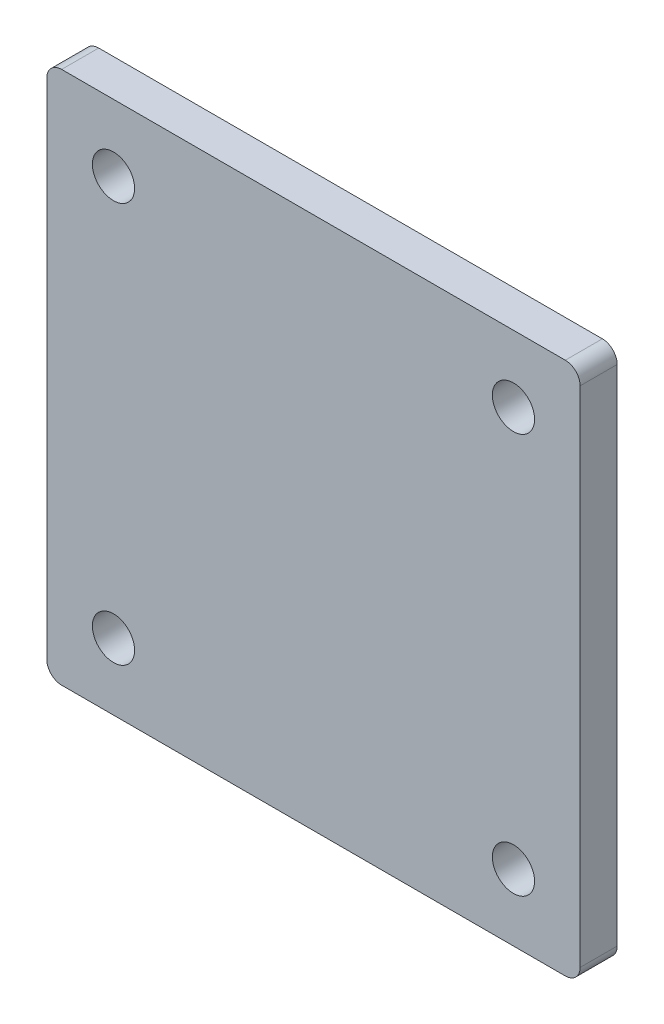
SolidWorks part; units mm, degrees
ref_plane "Front" through (0, 0, 0) normal (0, 0, 1) x (1, 0, 0)
ref_plane "Top" through (0, 0, 0) normal (0, 1, 0) x (1, 0, 0)
ref_plane "Right" through (0, 0, 0) normal (1, 0, 0) x (0, 0, -1)
sketch "Sketch1" plane through (0, 0, 0) normal (0, 0, 1) x (1, 0, 0)
  line L0 (-4.3033, 4.3033) -> (-36, 36) construction
  line L1 (36, -36) -> (-36, -36)
  line L2 (36, -36) -> (36, 36)
  line L3 (36, 36) -> (-36, 36)
  line L4 (-36, -36) -> (-36, 36)
  line L6 (36, 36) -> (24.9847, 24.9847) construction
  line L7 (-5.2963, -5.2963) -> (-36, -36) construction
  circle A0 centre (-27, 27) radius 2.85
  circle A1 centre (27, 27) radius 2.85
  circle A2 centre (27, -27) radius 2.85
  circle A3 centre (-27, -27) radius 2.85
  point P0 (0, 0)
  dimension "D3" = 36
  dimension "D4" = 5.7
  dimension "D6" = 9
  dimension "D1" = 72
  dimension "D2" = 72
  dimension "D7" = 9
extrude "Boss-Extrude1" add sketch "Sketch1" along normal blind 5
fillet "Fillet1" radius 2 1 edges at (-36, 36, 2.5)
fillet "Fillet2" radius 2 3 edges at (-36, -36, 2.5) (36, -36, 2.5) (36, 36, 2.5)
sketch "Sketch2" plane through (0, 0, 0) normal (0, 0, -1) x (-1, 0, 0)
